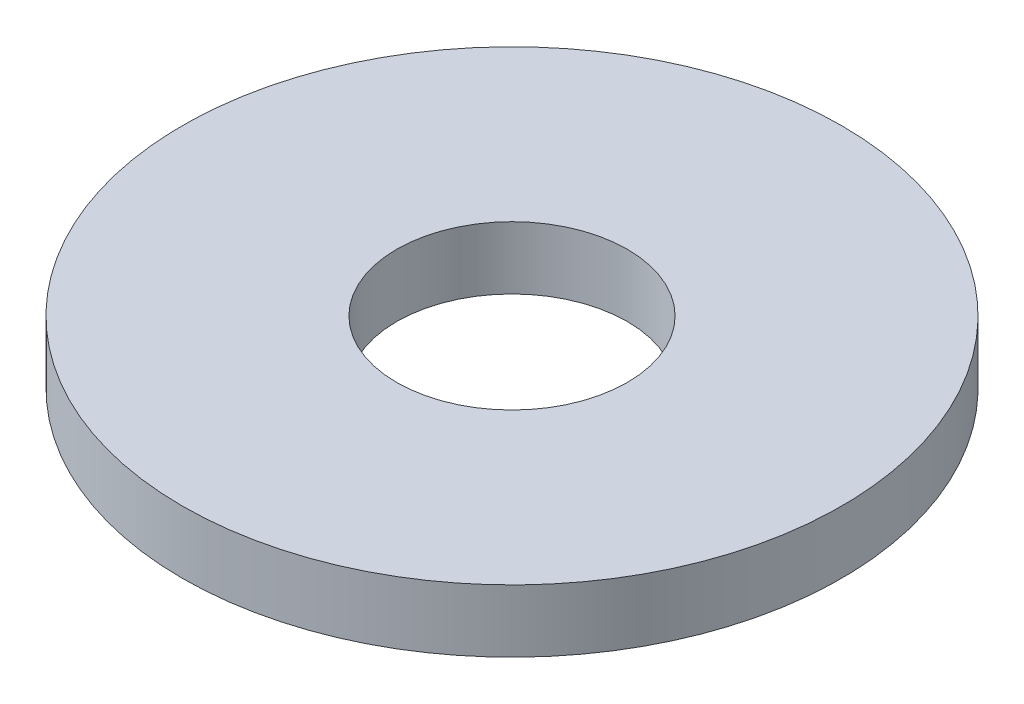
SolidWorks part; units mm, degrees
material "AISI 1010 Steel, hot rolled bar"
ref_plane "Alzado" through (0, 0, 0) normal (0, 0, 1) x (1, 0, 0)
ref_plane "Planta" through (0, 0, 0) normal (0, 1, 0) x (1, 0, 0)
ref_plane "Vista lateral" through (0, 0, 0) normal (1, 0, 0) x (0, 0, -1)
sketch "Sketch1" plane through (0, 0, 0) normal (0, 1, 0) x (1, 0, 0)
  circle A0 centre (0, 0) radius 1.75
  circle A1 centre (0, 0) radius 5
  dimension "D1" = 10
  dimension "D2" = 3.5
extrude "Boss-Extrude1" add sketch "Sketch1" along normal blind 0.95
